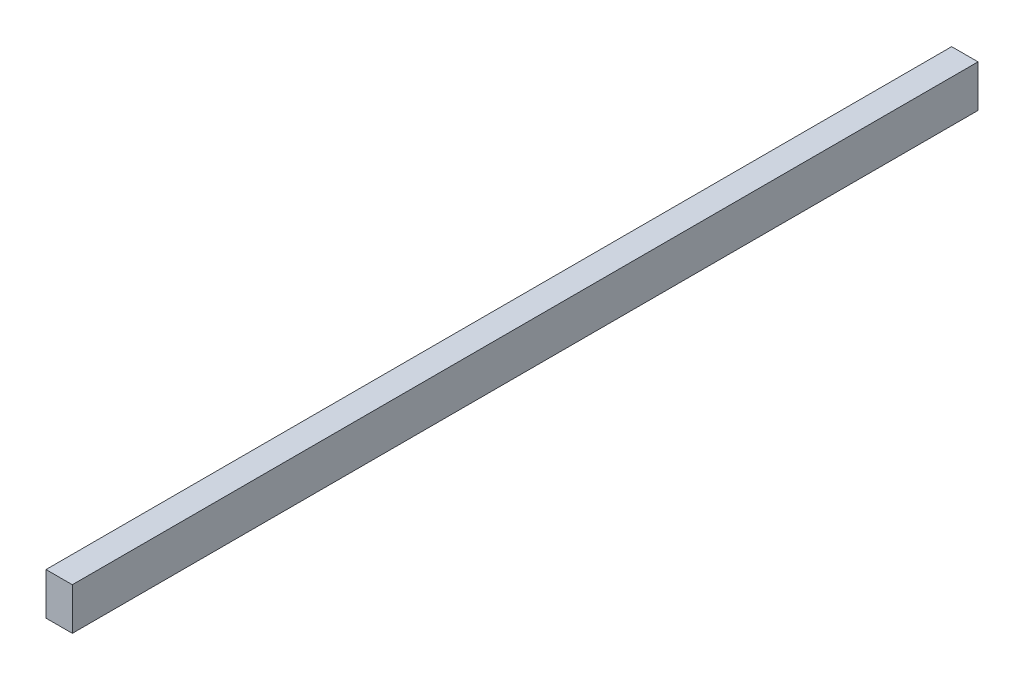
SolidWorks part; units mm, degrees
ref_plane "Alzado" through (0, 0, 0) normal (0, 0, 1) x (1, 0, 0)
ref_plane "Planta" through (0, 0, 0) normal (0, 1, 0) x (1, 0, 0)
ref_plane "Vista lateral" through (0, 0, 0) normal (1, 0, 0) x (0, 0, -1)
sketch "Croquis_travesano" plane through (0, 0, 0) normal (0, 1, 0) x (1, 0, 0)
  line L1 (-12.5, -430) -> (12.5, -430)
  line L2 (-12.5, -430) -> (-12.5, 430)
  line L3 (-12.5, 430) -> (12.5, 430)
  line L4 (12.5, -430) -> (12.5, 430)
  line L5 (-12.5, -430) -> (12.5, 430) construction
  line L6 (-12.5, 430) -> (12.5, -430) construction
  point P0 (0, 0)
  dimension "D1" = 12.5
  dimension "D2" = 430
extrude "Travesano_corto" add sketch "Croquis_travesano" along normal blind 40
